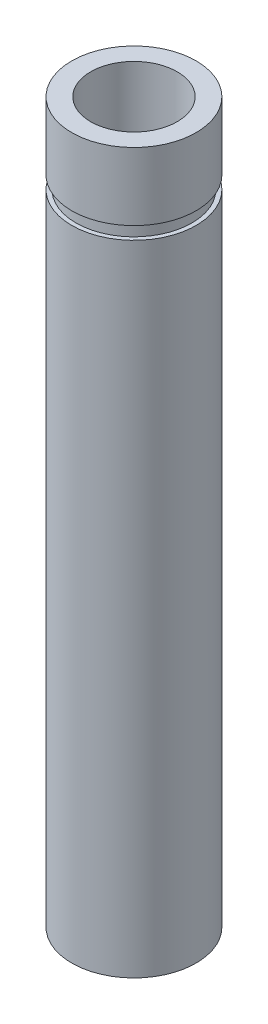
SolidWorks part; units mm, degrees
material "ASTM A36 Acero"
ref_plane "Alzado" through (0, 0, 0) normal (0, 0, 1) x (1, 0, 0)
ref_plane "Planta" through (0, 0, 0) normal (0, 1, 0) x (1, 0, 0)
ref_plane "Vista lateral" through (0, 0, 0) normal (1, 0, 0) x (0, 0, -1)
sketch "Croquis1" plane through (0, 0, 0) normal (0, 0, 1) x (1, 0, 0)
  line L0 (-13.9199, -136.5234) -> (-13.9199, 33.4766)
  dimension "D1" = 170
other "Miembro estructural1"
ref_plane "Plano1" through (-13.9199, -136.5234, 0) normal (0, 1, 0) x (-1, 0, 0)
sketch "Sketch12" plane through (-13.9199, -136.5234, 0) normal (0, 1, 0) x (-1, 0, 0)
  circle A0 centre (0, 0) radius 10.23
  circle A1 centre (0, 0) radius 16
  circle A2 centre (0, 0) radius 9.73 construction
  point P5 (0, 0)
  dimension "In_dia" = 20.46
  dimension "Out_dia" = 32
  dimension "D1" = 19.46
sketch "Croquis2" plane through (0, 0, 0) normal (0, 0, 1) x (1, 0, 0)
  line L0 (0.7801, 33.4766) -> (15.9392, 33.4766)
  line L1 (2.0801, 33.4766) -> (-29.9199, 33.4766) construction
  line L2 (15.9392, 33.4766) -> (15.9392, -136.5234)
  line L3 (15.9392, -136.5234) -> (0.7801, -136.5234)
  line L4 (0.7801, 33.4766) -> (0.7801, -136.5234)
  line L5 (-29.9199, -136.5234) -> (2.0801, -136.5234) construction
  line L6 (2.0801, -136.5234) -> (2.0801, 33.4766) construction
  line L7 (-13.9199, 33.4766) -> (-13.9199, -136.5234) construction
  line L8 (-3.6899, 33.4766) -> (-24.1499, 33.4766) construction
  dimension "D1" = 1.3
revolve "Cortar-Revolución1" cut sketch "Croquis2" angle 360 about L7
sketch "Croquis3" plane through (0, 0, 0) normal (0, 0, 1) x (1, 0, 0)
  line L0 (0.7801, -136.5234) -> (0.7801, 33.4766) construction
  line L1 (0.7801, 17.4766) -> (-0.2199, 17.4766)
  line L2 (0.7801, 17.4766) -> (0.7801, 14.4766)
  line L3 (0.7801, 14.4766) -> (-0.2199, 14.4766)
  line L4 (-0.2199, 17.4766) -> (-0.2199, 14.4766)
  line L5 (-13.9199, 33.4766) -> (-13.9199, 14.9046) construction
  line L6 (0.7801, 33.4766) -> (-28.6199, 33.4766) construction
  line L7 (-28.6199, -136.5234) -> (0.7801, -136.5234) construction
  dimension "D1" = 1
  dimension "D2" = 3
  dimension "D3" = 151
revolve "Cortar-Revolución2" cut sketch "Croquis3" angle 360 about L5
